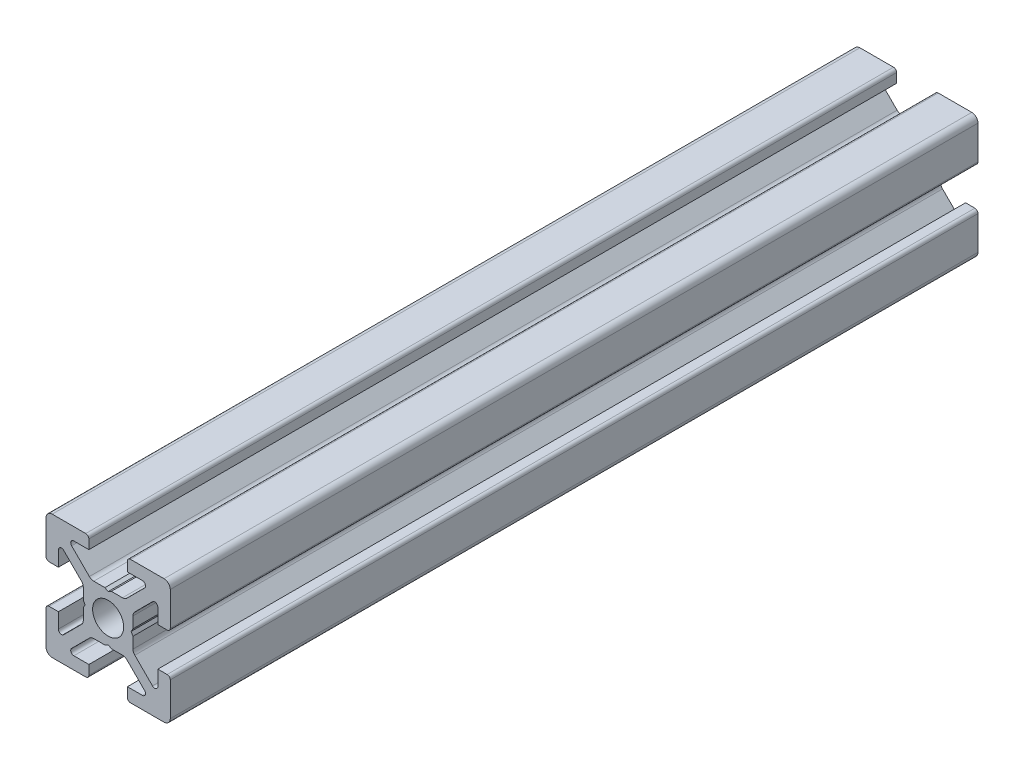
SolidWorks part; units mm, degrees
ref_plane "前视基准面" through (0, 0, 0) normal (0, 0, 1) x (1, 0, 0)
ref_plane "上视基准面" through (0, 0, 0) normal (0, 1, 0) x (1, 0, 0)
ref_plane "右视基准面" through (0, 0, 0) normal (1, 0, 0) x (0, 0, -1)
sketch "草图1" plane through (0, 0, 0) normal (0, 0, 1) x (1, 0, 0)
  line L0 (16.4868, 27.1233) -> (19.3403, 24.2698)
  line L1 (20.1939, 24.6233) -> (20.1939, 27.0434)
  line L2 (20.1939, 27.0434) -> (21.6939, 27.0434)
  line L3 (15.8939, 30.1434) -> (16.1939, 29.6238)
  line L4 (12.1939, 33.8434) -> (12.7135, 34.1434)
  line L5 (22.1939, 26.5434) -> (22.1939, 21.1434)
  line L6 (21.1939, 20.1434) -> (15.7939, 20.1434)
  line L7 (12.1939, 33.8434) -> (11.6743, 34.1434)
  line L8 (12.7135, 34.1434) -> (14.5069, 34.1434)
  line L9 (15.2939, 20.6434) -> (15.2939, 22.1434)
  line L10 (15.2939, 22.1434) -> (17.714, 22.1434)
  line L11 (18.0675, 22.997) -> (15.214, 25.8506)
  line L12 (14.5069, 26.1434) -> (12.7135, 26.1434)
  line L13 (9.1738, 25.8506) -> (6.3202, 22.997)
  line L14 (6.6738, 22.1434) -> (9.0939, 22.1434)
  line L15 (9.0939, 22.1434) -> (9.0939, 20.6434)
  line L16 (15.8939, 30.1434) -> (16.1939, 30.6631)
  line L17 (12.1939, 26.4434) -> (11.6743, 26.1434)
  line L18 (8.5939, 20.1434) -> (3.1939, 20.1434)
  line L19 (2.1939, 21.1434) -> (2.1939, 26.5434)
  line L20 (12.1939, 26.4434) -> (12.7135, 26.1434)
  line L21 (8.4939, 30.1434) -> (8.1939, 30.6631)
  line L22 (2.6939, 27.0434) -> (4.1939, 27.0434)
  line L23 (4.1939, 27.0434) -> (4.1939, 24.6233)
  line L24 (5.0474, 24.2698) -> (7.901, 27.1233)
  line L25 (8.1939, 27.8305) -> (8.1939, 29.6238)
  line L26 (7.901, 33.1635) -> (5.0474, 36.0171)
  line L27 (4.1939, 35.6635) -> (4.1939, 33.2434)
  line L28 (4.1939, 33.2434) -> (2.6939, 33.2434)
  line L29 (8.4939, 30.1434) -> (8.1939, 29.6238)
  line L30 (16.1939, 29.6238) -> (16.1939, 27.8305)
  line L31 (2.1939, 33.7434) -> (2.1939, 39.1434)
  line L32 (3.1939, 40.1434) -> (8.5939, 40.1434)
  line L33 (11.6743, 26.1434) -> (9.8809, 26.1434)
  line L34 (8.1939, 30.6631) -> (8.1939, 32.4564)
  line L35 (9.0939, 39.6434) -> (9.0939, 38.1434)
  line L36 (9.0939, 38.1434) -> (6.6738, 38.1434)
  line L37 (6.3202, 37.2899) -> (9.1738, 34.4363)
  line L38 (9.8809, 34.1434) -> (11.6743, 34.1434)
  line L39 (15.214, 34.4363) -> (18.0675, 37.2899)
  line L40 (17.714, 38.1434) -> (15.2939, 38.1434)
  line L41 (15.2939, 38.1434) -> (15.2939, 39.6434)
  line L44 (15.7939, 40.1434) -> (21.1939, 40.1434)
  line L45 (22.1939, 39.1434) -> (22.1939, 33.7434)
  line L48 (21.6939, 33.2434) -> (20.1939, 33.2434)
  line L49 (20.1939, 33.2434) -> (20.1939, 35.6635)
  line L50 (19.3403, 36.0171) -> (16.4868, 33.1635)
  line L51 (16.1939, 32.4564) -> (16.1939, 30.6631)
  circle A0 centre (12.1939, 30.1434) radius 2.5
  arc A1 (16.1939, 27.8305) -> (16.4868, 27.1233) centre (17.1939, 27.8305) ccw
  arc A2 (19.3403, 24.2698) -> (20.1939, 24.6233) centre (19.6939, 24.6233) ccw
  arc A3 (21.1939, 20.1434) -> (22.1939, 21.1434) centre (21.1939, 21.1434) ccw
  arc A4 (17.714, 22.1434) -> (18.0675, 22.997) centre (17.714, 22.6434) ccw
  arc A5 (15.214, 25.8506) -> (14.5069, 26.1434) centre (14.5069, 25.1434) ccw
  arc A6 (9.8809, 26.1434) -> (9.1738, 25.8506) centre (9.8809, 25.1434) ccw
  arc A7 (6.3202, 22.997) -> (6.6738, 22.1434) centre (6.6738, 22.6434) ccw
  arc A8 (2.1939, 21.1434) -> (3.1939, 20.1434) centre (3.1939, 21.1434) ccw
  arc A9 (4.1939, 24.6233) -> (5.0474, 24.2698) centre (4.6939, 24.6233) ccw
  arc A10 (7.901, 27.1233) -> (8.1939, 27.8305) centre (7.1939, 27.8305) ccw
  arc A11 (8.1939, 32.4564) -> (7.901, 33.1635) centre (7.1939, 32.4564) ccw
  arc A12 (5.0474, 36.0171) -> (4.1939, 35.6635) centre (4.6939, 35.6635) ccw
  arc A13 (3.1939, 40.1434) -> (2.1939, 39.1434) centre (3.1939, 39.1434) ccw
  arc A14 (6.6738, 38.1434) -> (6.3202, 37.2899) centre (6.6738, 37.6434) ccw
  arc A15 (9.1738, 34.4363) -> (9.8809, 34.1434) centre (9.8809, 35.1434) ccw
  arc A16 (14.5069, 34.1434) -> (15.214, 34.4363) centre (14.5069, 35.1434) ccw
  arc A17 (18.0675, 37.2899) -> (17.714, 38.1434) centre (17.714, 37.6434) ccw
  arc A18 (22.1939, 39.1434) -> (21.1939, 40.1434) centre (21.1939, 39.1434) ccw
  arc A19 (20.1939, 35.6635) -> (19.3403, 36.0171) centre (19.6939, 35.6635) ccw
  arc A20 (16.4868, 33.1635) -> (16.1939, 32.4564) centre (17.1939, 32.4564) ccw
  arc A21 (15.7939, 20.1434) -> (15.2939, 20.6434) centre (15.7939, 20.6434) cw
  arc A22 (9.0939, 20.6434) -> (8.5939, 20.1434) centre (8.5939, 20.6434) cw
  arc A23 (2.1939, 26.5434) -> (2.6939, 27.0434) centre (2.6939, 26.5434) cw
  arc A24 (2.6939, 33.2434) -> (2.1939, 33.7434) centre (2.6939, 33.7434) cw
  arc A25 (22.1939, 26.5434) -> (21.6939, 27.0434) centre (21.6939, 26.5434) ccw
  arc A26 (21.6939, 33.2434) -> (22.1939, 33.7434) centre (21.6939, 33.7434) ccw
  arc A27 (15.7939, 40.1434) -> (15.2939, 39.6434) centre (15.7939, 39.6434) ccw
  arc A28 (9.0939, 39.6434) -> (8.5939, 40.1434) centre (8.5939, 39.6434) ccw
  dimension "D1" = 0.5
  dimension "D2" = 4
extrude "凸台-拉伸1" add sketch "草图1" along normal blind 130
